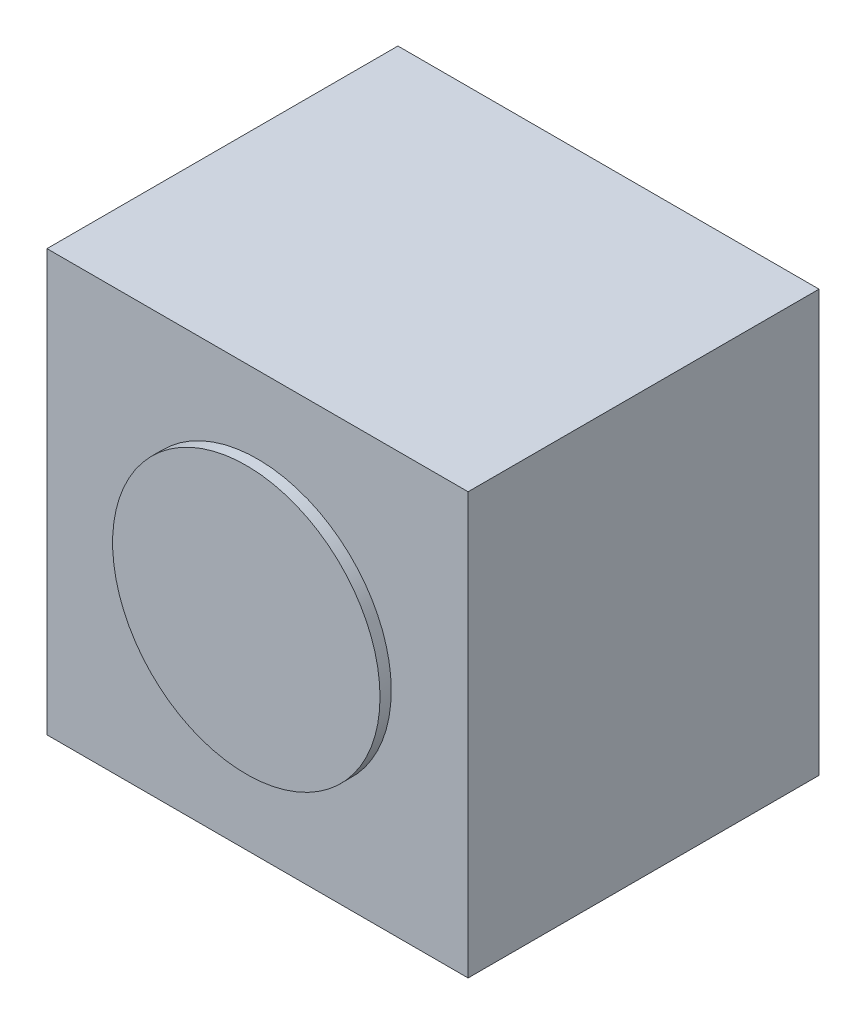
SolidWorks part; units mm, degrees
ref_plane "정면" through (0, 0, 0) normal (0, 0, 1) x (1, 0, 0)
ref_plane "윗면" through (0, 0, 0) normal (0, 1, 0) x (1, 0, 0)
ref_plane "우측면" through (0, 0, 0) normal (1, 0, 0) x (0, 0, -1)
sketch "스케치1" plane through (0, 0, 0) normal (0, 0, 1) x (1, 0, 0)
  line L1 (-30, 30) -> (30, 30)
  line L2 (-30, 30) -> (-30, -30)
  line L3 (-30, -30) -> (30, -30)
  line L4 (30, 30) -> (30, -30)
  line L5 (-30, 30) -> (30, -30) construction
  line L6 (-30, -30) -> (30, 30) construction
  point P0 (0, 0)
  dimension "D1" = 60
  dimension "D2" = 60
extrude "보스-돌출1" add sketch "스케치1" along normal blind 50
sketch "스케치2" plane through (0, 0, 50) normal (0, 0, 1) x (1, 0, 0)
  circle A0 centre (0, 0) radius 19.05
  dimension "D1" = 38.1
extrude "보스-돌출2" add sketch "스케치2" along normal blind 1.6
sketch "스케치3" plane through (0, 0, 51.6) normal (0, 0, 1) x (1, 0, 0)
  circle A0 centre (0, 0) radius 3.75
  dimension "D1" = 7.5
